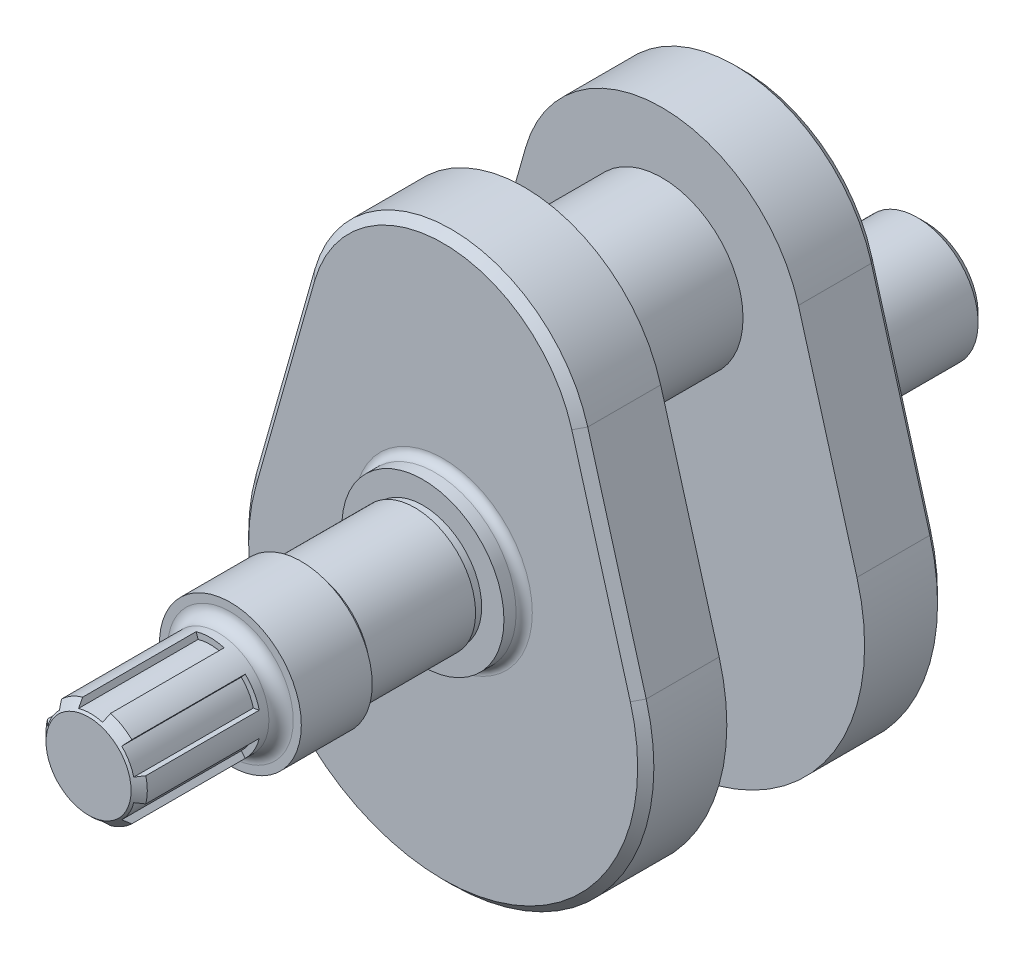
SolidWorks part; units mm, degrees
ref_plane "Front Plane" through (0, 0, 0) normal (0, 0, 1) x (1, 0, 0)
ref_plane "Top Plane" through (0, 0, 0) normal (0, 1, 0) x (1, 0, 0)
ref_plane "Right Plane" through (0, 0, 0) normal (1, 0, 0) x (0, 0, -1)
sketch "Sketch1" plane through (0, 0, 0) normal (0, 0, 1) x (1, 0, 0)
  circle A0 centre (0, 0) radius 20
  dimension "D1" = 40
extrude "Boss-Extrude1" add sketch "Sketch1" along normal mid plane 34
sketch "Sketch2" plane through (0, 0, 17) normal (0, 0, 1) x (1, 0, 0)
  line L0 (0, 0) -> (0, -20) construction
  line L1 (-33.6732, 9.5455) -> (-48.1046, -41.3636)
  line L2 (33.6732, 9.5455) -> (48.1046, -41.3636)
  line L3 (0, -35) -> (0, -55) construction
  arc A0 (-48.1046, -41.3636) -> (48.1046, -41.3636) centre (0, -55) ccw
  arc A1 (33.6732, 9.5455) -> (-33.6732, 9.5455) centre (0, 0) ccw
  dimension "D2" = 70
  dimension "D3" = 100
  dimension "D1" = 55
extrude "Boss-Extrude2" add sketch "Sketch2" along normal blind 20
chamfer "Chamfer1" distance 2 angle 45 4 edges at (40.8889, -15.9091, 37) (0, -105, 37) (-40.8889, -15.9091, 37) (0, 35, 37)
sketch "Sketch3" plane through (0, 0, 37) normal (0, 0, 1) x (1, 0, 0)
  line L0 (0, 0) -> (0, -35) construction
  circle A0 centre (0, -35) radius 20
  dimension "D2" = 40
  dimension "D1" = 35
extrude "Boss-Extrude3" add sketch "Sketch3" along normal blind 5
fillet "Fillet1" radius 2 1 edges at (20, -35, 37)
mirror "Mirror1" about plane through (0, 0, 0) normal (0, 0, 1) of "Fillet1", "Boss-Extrude3", "Chamfer1", "Boss-Extrude2"
sketch "Sketch4" plane through (0, 0, 42) normal (0, 0, 1) x (1, 0, 0)
  circle A0 centre (0, -35) radius 14.5
  dimension "D1" = 29
extrude "Boss-Extrude4" add sketch "Sketch4" along normal blind 2
sketch "Sketch5" plane through (0, 0, 44) normal (0, 0, 1) x (1, 0, 0)
  circle A0 centre (0, -35) radius 15
  dimension "D1" = 30
extrude "Boss-Extrude5" add sketch "Sketch5" along normal blind 26
sketch "Sketch6" plane through (0, 0, 70) normal (0, 0, 1) x (1, 0, 0)
  circle A0 centre (0, -35) radius 14.5
  dimension "D1" = 29
extrude "Boss-Extrude6" add sketch "Sketch6" along normal blind 2
sketch "Sketch7" plane through (0, 0, -42) normal (0, 0, -1) x (-1, 0, 0)
  circle A0 centre (0, -35) radius 15
  dimension "D1" = 30
extrude "Boss-Extrude7" add sketch "Sketch7" along normal blind 40
fillet "Fillet2" radius 2 1 edges at (-15, -35, -42)
chamfer "Chamfer2" distance 2 angle 45 1 edges at (-15, -35, -82)
sketch "Sketch8" plane through (0, 0, 72) normal (0, 0, 1) x (1, 0, 0)
  circle A0 centre (0, -35) radius 17.5
  dimension "D1" = 35
extrude "Boss-Extrude8" add sketch "Sketch8" along normal blind 17.5
sketch "Sketch9" plane through (0, 0, 89.5) normal (0, 0, 1) x (1, 0, 0)
  circle A0 centre (0, -35) radius 12.5
  dimension "D1" = 25
extrude "Boss-Extrude9" add sketch "Sketch9" along normal blind 35
fillet "Fillet3" radius 3 1 edges at (12.5, -35, 89.5)
chamfer "Chamfer3" distance 2 angle 45 1 edges at (12.5, -35, 124.5)
sketch "Sketch10" plane through (0, 0, 124.5) normal (0, 0, 1) x (1, 0, 0)
  line L0 (0, -24) -> (0, 0) construction
  line L1 (0, -35) -> (-44.2218, -35) construction
  line L2 (-31.749, 9) -> (-46.1804, -41.9091) construction
  line L3 (-3.4544, -22.9868) -> (-2.9629, -24.4066)
  line L4 (3.4544, -22.9868) -> (2.9629, -24.4066)
  line L5 (0, -24) -> (0, -35) construction
  arc A0 (2.9629, -24.4066) -> (-2.9629, -24.4066) centre (0, -35) ccw
  arc A1 (3.4544, -22.9868) -> (-3.4544, -22.9868) centre (0, -35) ccw
  circle A2 centre (0, -35) radius 12.5 construction
  dimension "D1" = 22
  dimension "D2" = 6
  dimension "D3" = 7
extrude "Cut-Extrude1" cut sketch "Sketch10" against normal blind 30
pattern_circular "CirPattern1" count 6 over 360 about axis through (0, -35, 0) along (0, 0, 1) of "Cut-Extrude1"
